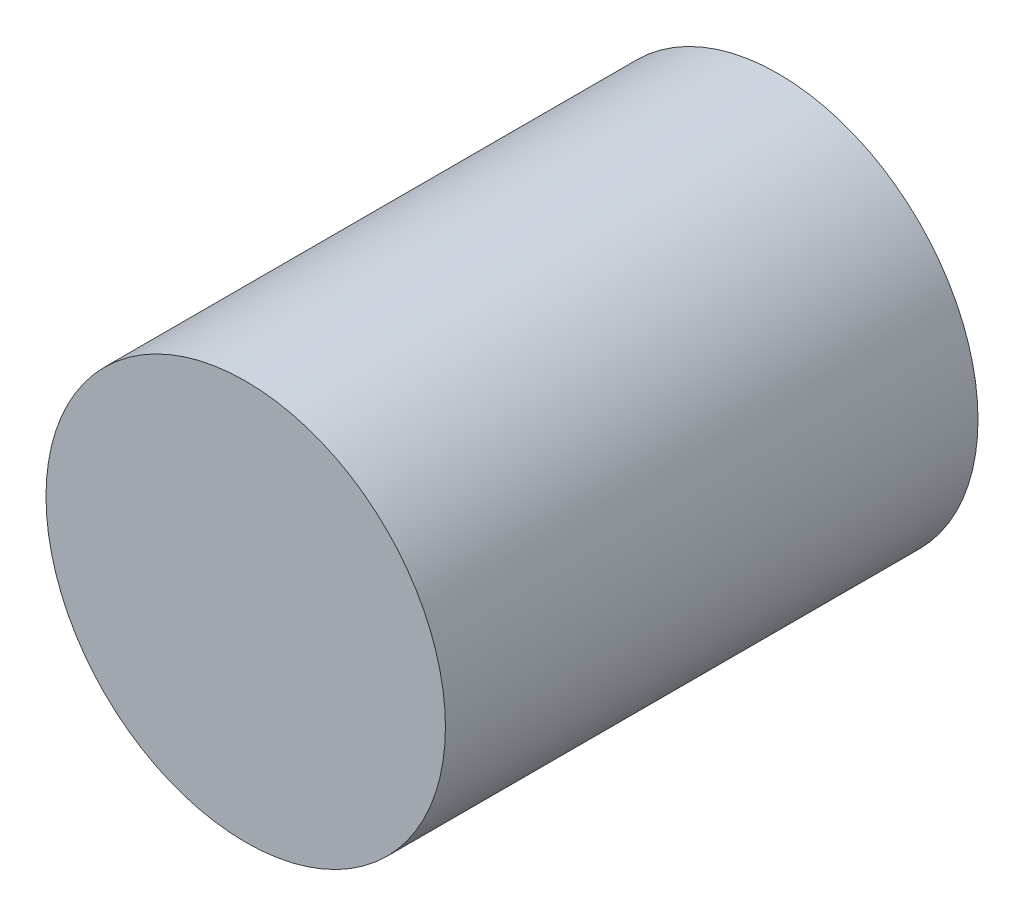
SolidWorks part; units mm, degrees
ref_plane "前视基准面" through (0, 0, 0) normal (0, 0, 1) x (1, 0, 0)
ref_plane "上视基准面" through (0, 0, 0) normal (0, 1, 0) x (1, 0, 0)
ref_plane "右视基准面" through (0, 0, 0) normal (1, 0, 0) x (0, 0, -1)
sketch "草图1" plane through (0, 0, 0) normal (0, 0, 1) x (1, 0, 0)
  circle A0 centre (-25, -30) radius 7.5
  dimension "D1" = 15
extrude "凸台-拉伸1" add sketch "草图1" along normal blind 20
